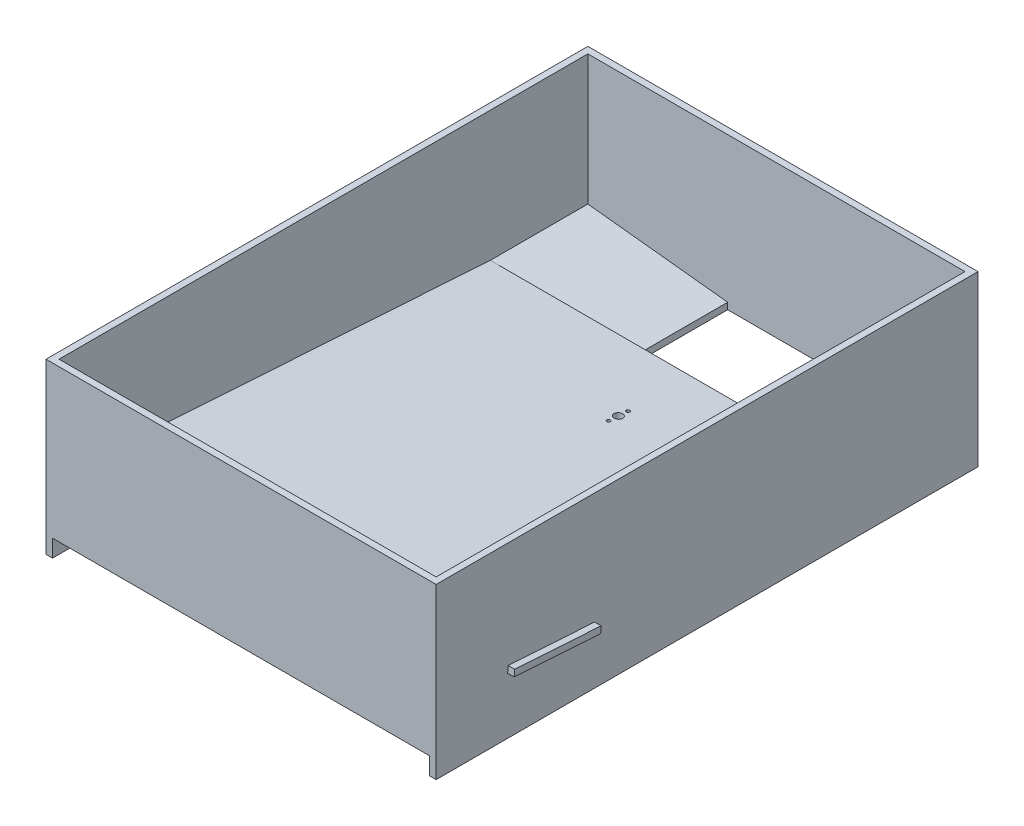
SolidWorks part; units mm, degrees
ref_plane "前视基准面" through (0, 0, 0) normal (0, 0, 1) x (1, 0, 0)
ref_plane "上视基准面" through (0, 0, 0) normal (0, 1, 0) x (1, 0, 0)
ref_plane "右视基准面" through (0, 0, 0) normal (1, 0, 0) x (0, 0, -1)
sketch "草图1" plane through (0, 0, 0) normal (0, 1, 0) x (1, 0, 0)
  line L1 (-90, 125) -> (90, 125)
  line L2 (-90, 125) -> (-90, -125)
  line L3 (-90, -125) -> (90, -125)
  line L4 (90, 125) -> (90, -125)
  line L5 (-90, 125) -> (90, -125) construction
  line L6 (-90, -125) -> (90, 125) construction
  point P0 (0, 0)
  dimension "D1" = 180
  dimension "D2" = 250
extrude "凸台-拉伸1" add sketch "草图1" along normal blind 70
shell "抽壳1" thickness 3
sketch "草图3" plane through (-87, 0, 0) normal (1, 0, 0) x (0, 0, -1)
  line L0 (-122, 23) -> (77, 10)
  line L1 (-122, 70) -> (-122, 0) construction
  line L3 (77, 10) -> (77, 6.9936)
  line L4 (77, 6.9936) -> (-122, 19.9936)
  line L5 (-122, 19.9936) -> (-122, 23)
  line L7 (122, 70) -> (122, 0) construction
  line L8 (-125, 0) -> (125, 0) construction
  dimension "D1" = 3
  dimension "D2" = 23
  dimension "D3" = 45
  dimension "D4" = 10
extrude "凸台-拉伸2" add sketch "草图3" along normal up to next
sketch "草图4" plane through (0, 0, -122) normal (0, 0, 1) x (1, 0, 0)
  line L0 (-87, 10) -> (-87, 7)
  line L1 (-87, 70) -> (-87, 0) construction
  line L2 (-87, 7) -> (-22.5, 0)
  line L4 (-22.5, 0) -> (-22.5, 3)
  line L5 (-22.5, 3) -> (-87, 10)
  line L6 (-22.5, 3) -> (22.5, 3) construction
  line L7 (0, 3) -> (0, 0) construction
  line L8 (87, 10) -> (-87, 10) construction
  line L9 (22.5, 3) -> (87, 10)
  line L10 (87, 70) -> (87, 0) construction
  line L11 (87, 10) -> (87, 7)
  line L12 (87, 7) -> (22.5, 0)
  line L13 (22.5, 0) -> (22.5, 3)
  dimension "D1" = 45
extrude "凸台-拉伸3" add sketch "草图4" along normal up to surface (45 mm away) up to face at (0, 8.4968, -77)
sketch "草图5" plane through (0, 0, -77) normal (0, 0, 1) x (1, 0, 0)
  line L1 (-87, 6.9936) -> (87, 6.9936)
  line L2 (-87, 6.9936) -> (-87, 0)
  line L3 (-87, 0) -> (87, 0)
  line L4 (87, 6.9936) -> (87, 0)
extrude "凸台-拉伸6" add sketch "草图5" along normal blind 3 separate body
sketch "草图6" plane through (-87, 0, 0) normal (1, 0, 0) x (0, 0, -1)
  line L0 (-92, 18.0338) -> (-52.0851, 15.4263)
  line L1 (-122, 19.9936) -> (77, 6.9936) construction
  line L2 (-52.0851, 15.4263) -> (-51.8895, 18.4199)
  line L3 (-51.8895, 18.4199) -> (-91.8044, 21.0274)
  line L4 (-91.8044, 21.0274) -> (-92, 18.0338)
  line L5 (-122, 19.9936) -> (-122, 0) construction
  dimension "D1" = 30
  dimension "D2" = 40
  dimension "D3" = 3
extrude "凸台-拉伸7" add sketch "草图6" against normal offset from surface 3 and the other way offset from surface (180 mm away) 3 up to face at (-90, 35, 0) offset beyond the face yes other way up to face at (90, 35, 0)
sketch "草图12" plane through (0, 0, 0) normal (0, -1, 0) x (1, 0, 0)
  line L0 (90, -125) -> (-90, -125) construction
  line L1 (-90, 125) -> (-87, 125)
  line L2 (-90, 125) -> (-90, -125)
  line L3 (-90, -125) -> (-87, -125)
  line L4 (-87, 125) -> (-87, -125)
  line L5 (87, 122) -> (87, -122) construction
  line L6 (90, 125) -> (87, 125)
  line L7 (90, 125) -> (90, -125)
  line L8 (90, -125) -> (87, -125)
  line L9 (87, 125) -> (87, -125)
  line L10 (-87, -122) -> (-87, 122) construction
extrude "凸台-拉伸8" add sketch "草图12" along normal blind 8
sketch "草图13" plane through (0, 14.9663, -0.9777) normal (0, 0.9979, -0.0652) x (1, 0, 0)
  line L0 (7, 45.6843) -> (7, 36.6843) construction
  line L2 (87, 76.1843) -> (-87, 76.1843) construction
  line L3 (87, -123.2398) -> (87, 76.1843) construction
  circle A0 centre (7, 41.1843) radius 2
  circle A1 centre (7, 45.6843) radius 0.8
  circle A2 centre (7, 36.6843) radius 0.8
  dimension "D1" = 4
  dimension "D2" = 1.6
  dimension "D3" = 9
  dimension "D4" = 80
  dimension "D5" = 35
extrude "切除-拉伸1" cut sketch "草图13" against normal up to next (3 mm away)
